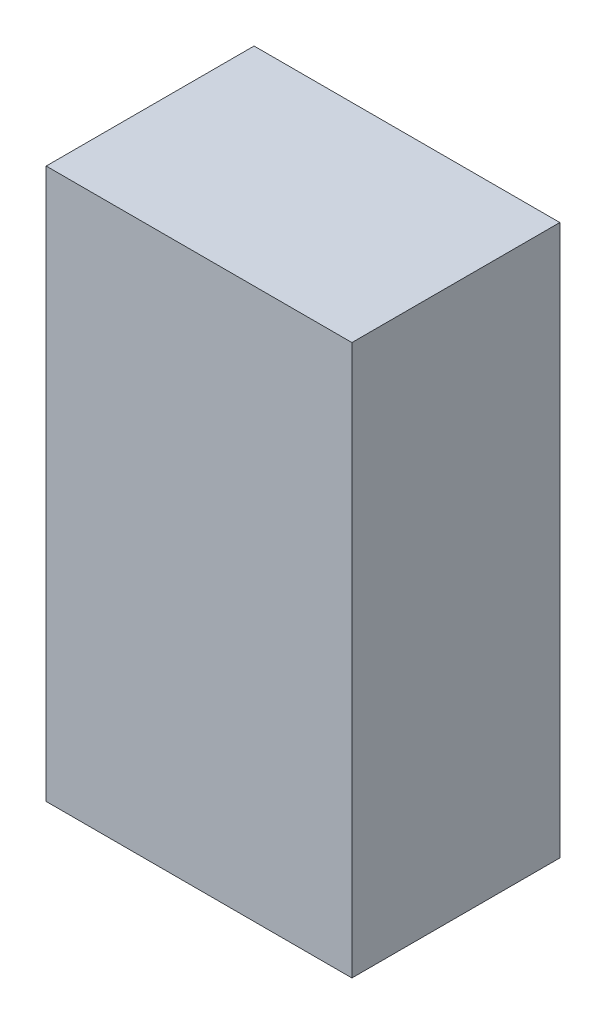
SolidWorks part; units mm, degrees
ref_plane "Front" through (0, 0, 0) normal (0, 0, 1) x (1, 0, 0)
ref_plane "Top" through (0, 0, 0) normal (0, 1, 0) x (1, 0, 0)
ref_plane "Right" through (0, 0, 0) normal (1, 0, 0) x (0, 0, -1)
sketch "Эскиз1" plane through (0, 0, 0) normal (0, 1, 0) x (1, 0, 0)
  line L1 (-12.5, 8.5) -> (12.5, 8.5)
  line L2 (-12.5, 8.5) -> (-12.5, -8.5)
  line L3 (-12.5, -8.5) -> (12.5, -8.5)
  line L4 (12.5, 8.5) -> (12.5, -8.5)
  line L5 (-12.5, 8.5) -> (12.5, -8.5) construction
  line L6 (-12.5, -8.5) -> (12.5, 8.5) construction
  point P0 (0, 0)
  dimension "D1" = 17
  dimension "D2" = 25
extrude "Бобышка-Вытянуть1" add sketch "Эскиз1" along normal blind 45
